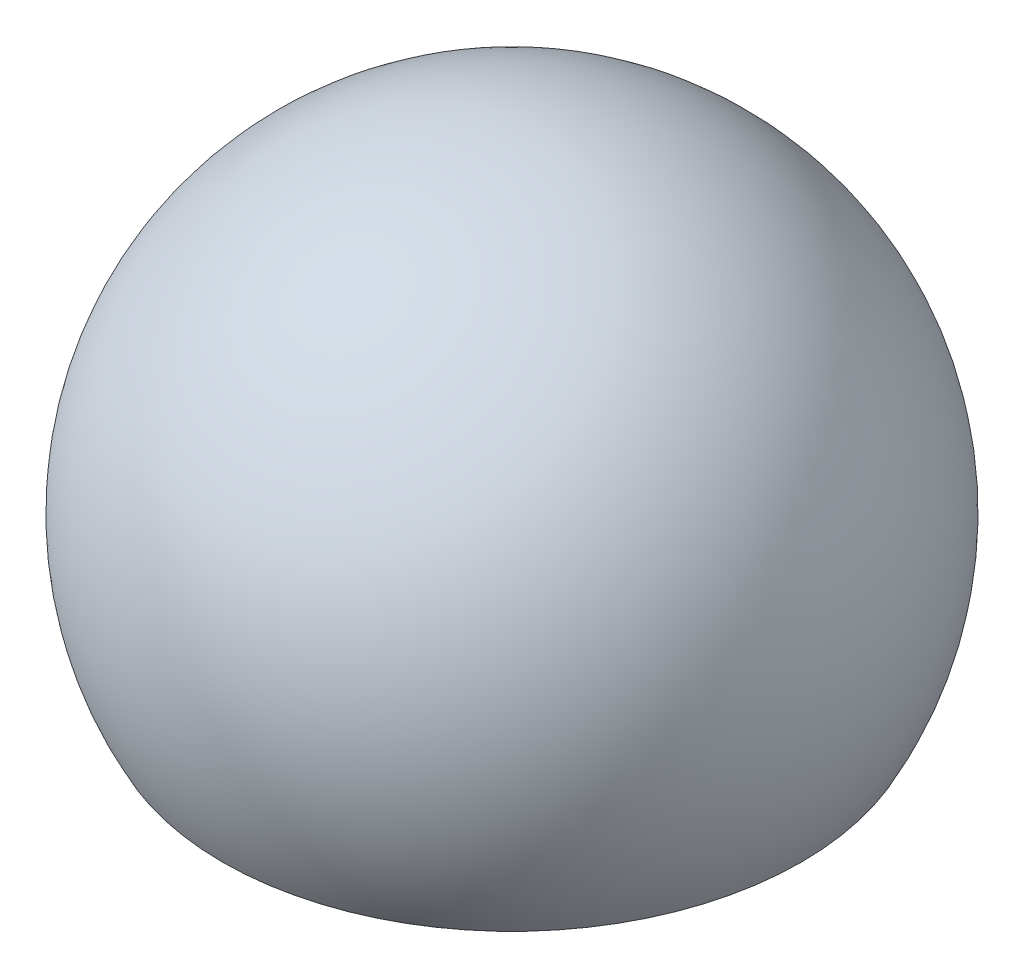
SolidWorks part; units mm, degrees
material "Glass"
ref_plane "Front Plane" through (0, 0, 0) normal (0, 0, 1) x (1, 0, 0)
ref_plane "Top Plane" through (0, 0, 0) normal (0, 1, 0) x (1, 0, 0)
ref_plane "Right Plane" through (0, 0, 0) normal (1, 0, 0) x (0, 0, -1)
sketch "Sketch1" plane through (0, 0, 0) normal (0, 0, 1) x (1, 0, 0)
  line L0 (-79, -43.1161) -> (-73.5, -43.1161)
  line L2 (0, 0) -> (0, 90) construction
  line L3 (0, 89.15) -> (0, 90) construction
  line L4 (0, 89.15) -> (0, 90)
  arc A0 (0, 90) -> (-79, -43.1161) centre (0, 0) ccw
  arc A1 (-73.5, -43.1161) -> (0, 89.15) centre (0, 2.595) cw
  dimension "D1" = 180
  dimension "D4" = 0.85
  dimension "D3" = 5.5
revolve "Revolve3" add sketch "Sketch1" angle 360 about L2
